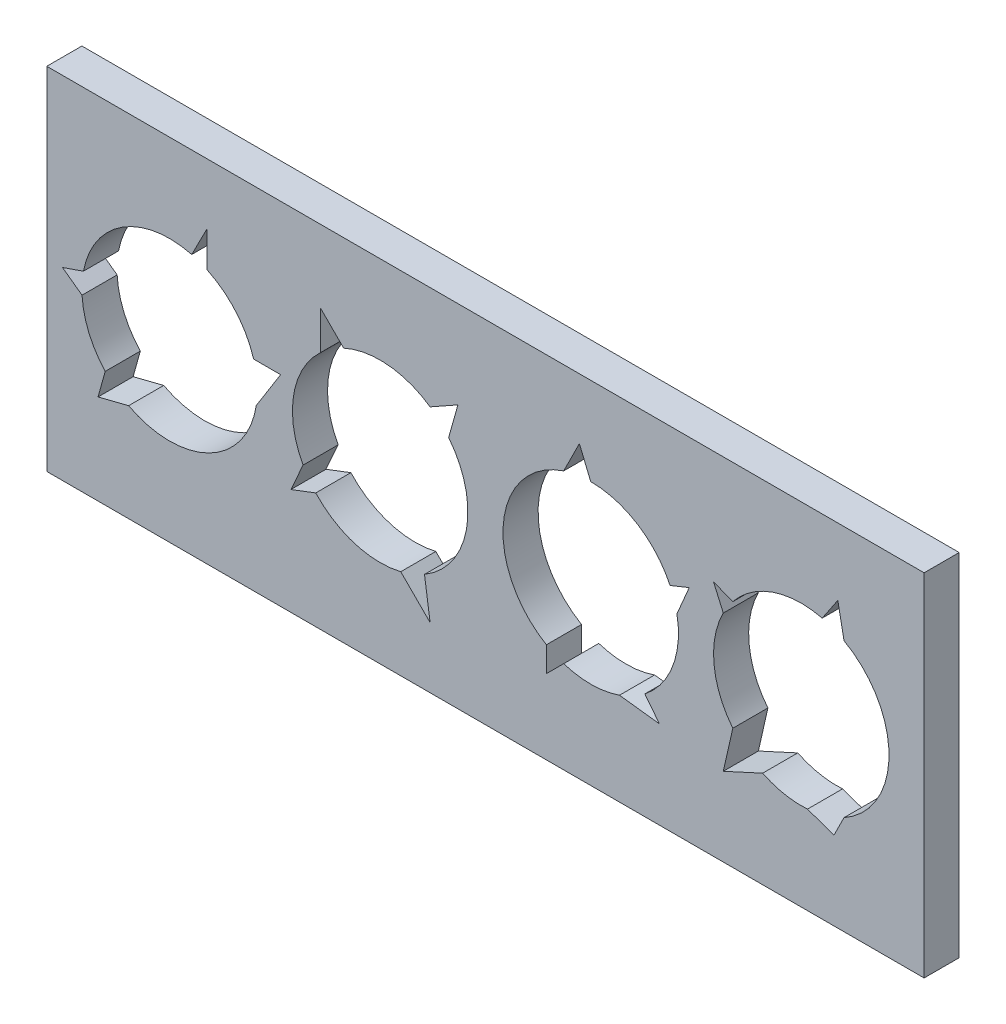
SolidWorks part; units mm, degrees
ref_plane "Front Plane" through (0, 0, 0) normal (0, 0, 1) x (1, 0, 0)
ref_plane "Top Plane" through (0, 0, 0) normal (0, 1, 0) x (1, 0, 0)
ref_plane "Right Plane" through (0, 0, 0) normal (1, 0, 0) x (0, 0, -1)
sketch "Sketch1" plane through (0, 0, 0) normal (0, 0, 1) x (1, 0, 0)
  line L0 (-49.5956, 55.7904) -> (-49.5956, 5.7904)
  line L1 (-84.5956, 55.7904) -> (165.4044, 55.7904)
  line L2 (-84.5956, 55.7904) -> (-84.5956, -44.2096)
  line L3 (-84.5956, -44.2096) -> (165.4044, -44.2096)
  line L4 (165.4044, 55.7904) -> (165.4044, -44.2096)
  line L5 (-49.5956, 5.7904) -> (-49.5956, -44.2096)
  line L6 (10.4044, 55.7904) -> (10.4044, 5.7904)
  line L7 (10.4044, 5.7904) -> (10.4044, -44.2096)
  line L8 (70.4044, 5.7904) -> (70.4044, 55.7904)
  line L9 (70.4044, 5.7904) -> (70.4044, -44.2096)
  line L10 (130.4044, 5.7904) -> (130.4044, 55.7904)
  line L11 (130.4044, 5.7904) -> (130.4044, -44.2096)
  line L12 (130.4044, 5.7904) -> (165.4044, 5.7904)
  line L13 (10.4044, 5.7904) -> (-49.5956, 5.7904)
  line L14 (10.4044, 5.7904) -> (70.4044, 5.7904)
  line L15 (70.4044, 5.7904) -> (130.4044, 5.7904)
  line L16 (-49.5956, 5.7904) -> (-84.5956, 5.7904)
  line L17 (24.6367, 26.3438) -> (32.5525, 30.7904)
  line L18 (32.5525, 30.7904) -> (29.9213, 21.4139)
  line L19 (16.2658, -18.5127) -> (24.6367, -26.8836)
  line L20 (24.6367, -26.8836) -> (23.034, -15.7849)
  line L21 (-11.5714, -6.1286) -> (-15.0424, -13.8898)
  line L22 (-15.0424, -13.8898) -> (-7.9518, -11.1815)
  line L23 (57.7748, -15.7849) -> (57.7748, -22.9165)
  line L24 (57.7748, -22.9165) -> (62.6989, -17.9924)
  line L25 (62.6989, 29.5733) -> (67.1712, 38.5487)
  line L26 (67.1712, 38.5487) -> (70.4044, 30.7904)
  line L27 (93.0126, 16.4614) -> (98.4741, 18.6607)
  line L28 (98.4741, 18.6607) -> (94.9698, 10.4315)
  line L29 (142.5798, 27.6253) -> (140.8183, 36.6875)
  line L30 (140.8183, 36.6875) -> (136.3559, 30.0717)
  line L31 (110.8876, 21.4139) -> (105.4044, 23.5497)
  line L32 (105.4044, 23.5497) -> (108.1783, 17.236)
  line L33 (142.5798, -16.0444) -> (139.7234, -21.8072)
  line L34 (139.7234, -21.8072) -> (132.1765, -19.1467)
  line L35 (-43.2965, 29.9839) -> (-38.9077, 38.5487)
  line L36 (-38.9077, 38.5487) -> (-38.9077, 28.3906)
  line L37 (-25.6571, 12.998) -> (-17.9622, 12.998)
  line L38 (-17.9622, 12.998) -> (-24.8946, 1.9355)
  line L39 (-67.9518, -11.1815) -> (-69.9881, -18.5127)
  line L40 (-69.9881, -18.5127) -> (-61.2752, -16.3136)
  line L41 (85.8215, -13.8898) -> (89.9888, -19.2096)
  line L42 (89.9888, -19.2096) -> (78.604, -17.8267)
  line L43 (0, 28.5225) -> (-6.5619, 35.0844)
  line L44 (-6.5619, 35.0844) -> (-6.5619, 24.1519)
  line L45 (-74.161, 10.4315) -> (-80.123, 8.3692)
  line L46 (-80.123, 8.3692) -> (-74.5526, 4.3249)
  line L47 (110.8876, -9.833) -> (108.1783, -21.8072)
  line L48 (108.1783, -21.8072) -> (119.4037, -16.6591)
  circle A0 centre (-49.5956, 5.7904) radius 25
  circle A1 centre (10.4044, 5.7904) radius 25
  circle A2 centre (70.4044, 5.7904) radius 25
  circle A3 centre (130.4044, 5.7904) radius 25
  point P69 (-17.9622, 12.998)
  point P71 (67.1712, 38.5487)
  point P72 (-80.123, 8.3692)
  dimension "D3" = 50
  dimension "D4" = 50
  dimension "D5" = 50
  dimension "D6" = 50
  dimension "D1" = 250
  dimension "D2" = 100
  dimension "D7" = 60
extrude "Boss-Extrude2" add sketch "Sketch1" along normal blind 10 contours A0 L0 L1 L2 L16 L46 L45 | A1 L6 L1 L0 A0 L35 L36 L37 L38 L13 L44 L43 | A2 L25 L26 L8 L1 L6 A1 L17 L18 L14 | A3 L10 L1 L8 A2 L27 L28 L15 L32 L31 | A3 L12 L4 L1 L10 L30 L29 | A3 L11 L3 L4 L12 L33 L34 | A3 L15 A2 L41 L42 L9 L3 L11 L48 L47 | A2 L14 A1 L20 L19 L7 L3 L9 L24 L23 | A1 L13 L38 A0 L5 L3 L7 L22 L21 | A0 L46 L16 L2 L3 L5 L40 L39
